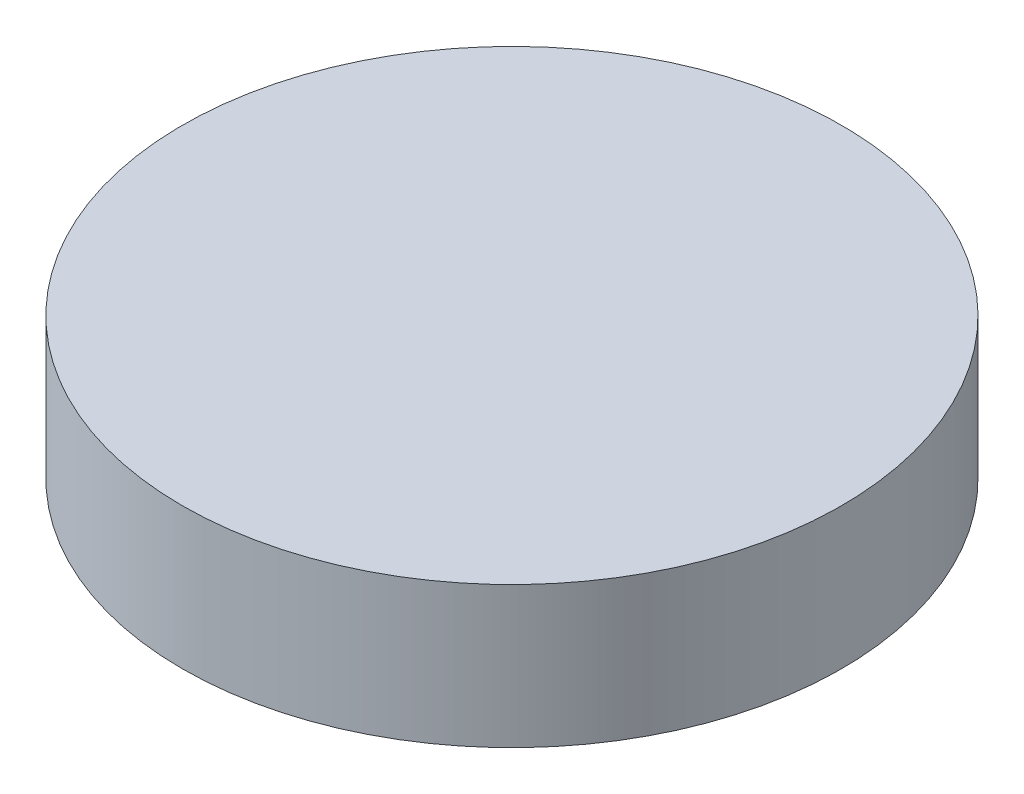
SolidWorks part; units mm, degrees
ref_plane "Front Plane" through (0, 0, 0) normal (0, 0, 1) x (1, 0, 0)
ref_plane "Top Plane" through (0, 0, 0) normal (0, 1, 0) x (1, 0, 0)
ref_plane "Right Plane" through (0, 0, 0) normal (1, 0, 0) x (0, 0, -1)
sketch "Sketch1" plane through (0, 0, 0) normal (0, 1, 0) x (1, 0, 0)
  circle A0 centre (0, 0) radius 14
  dimension "D1" = 28
extrude "Boss-Extrude1" add sketch "Sketch1" along normal blind 6
sketch "Sketch2" plane through (0, 0, 0) normal (0, 1, 0) x (1, 0, 0)
  circle A0 centre (0, 0) radius 2.5
  dimension "D1" = 5
extrude "Cut-Extrude1" cut sketch "Sketch2" along normal blind 2.4 draft 45
